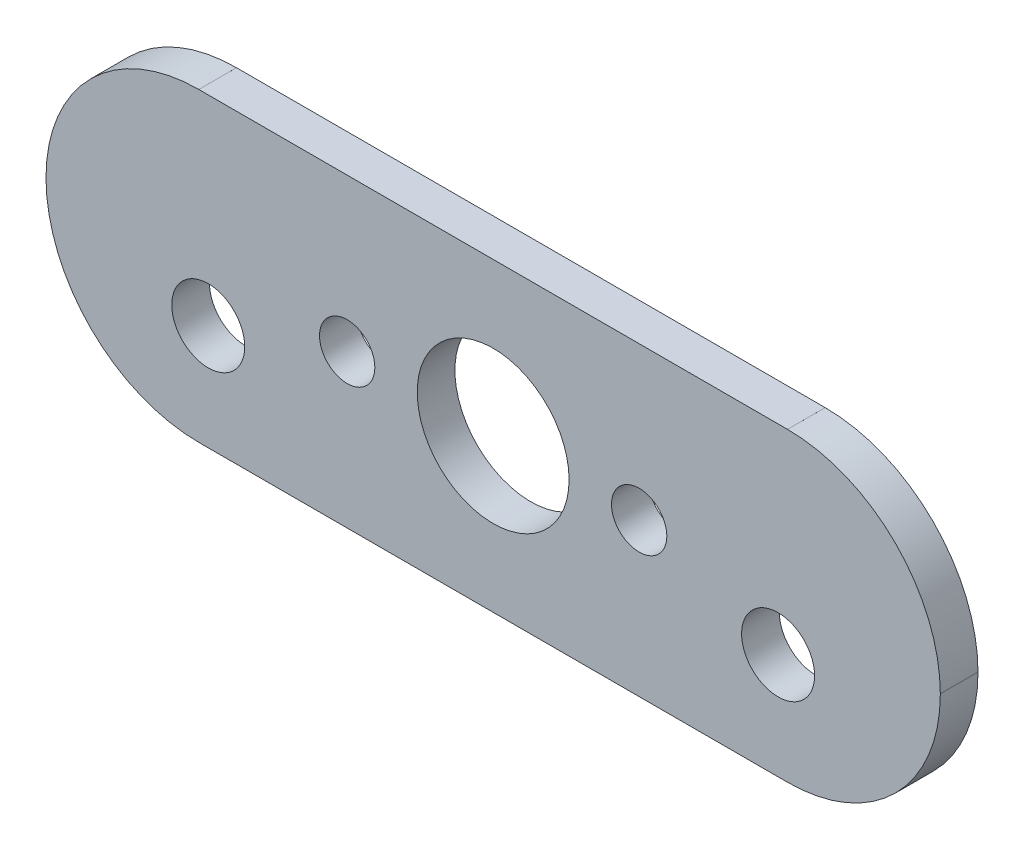
SolidWorks part; units mm, degrees
ref_plane "Alzado" through (0, 0, 0) normal (0, 0, 1) x (1, 0, 0)
ref_plane "Planta" through (0, 0, 0) normal (0, 1, 0) x (1, 0, 0)
ref_plane "Vista lateral" through (0, 0, 0) normal (1, 0, 0) x (0, 0, -1)
sketch "Model" plane through (0, 0, 0) normal (0, 0, 1) x (1, 0, 0)
  line L0 (18.99, 0.0199) -> (18.99, -0.0001)
  line L1 (12.5, 6.4901) -> (-12.5, 6.4901)
  line L2 (-18.9901, 0.01) -> (-18.9901, -0.01)
  line L3 (-12.5, -6.4902) -> (12.5, -6.4901)
  line L4 (0, -6.4902) -> (0, -7.9957) construction
  line L5 (0, 6.4901) -> (0, 6.0396)
  line L6 (0, 0) -> (0, 5.064) construction
  circle A0 centre (0, 0) radius 3.225
  circle A1 centre (-12.1, -2) radius 1.55
  circle A2 centre (12.1, -2) radius 1.55
  circle A3 centre (6.2, 0) radius 1.175
  circle A4 centre (-6.2, 0) radius 1.175
  arc A5 (12.5, -6.4901) -> (18.99, -0.0001) centre (12.4998, 0) ccw
  arc A6 (12.5, -6.4898) -> (12.5, -6.4904) centre (12.5, -6.4901) ccw
  arc A7 (20.6903, -0.01) -> (20.6898, -0.01) centre (20.6901, -0.01) ccw
  arc A8 (20.6898, -0.01) -> (20.6903, -0.01) centre (20.6901, -0.01) ccw
  arc A9 (20.6903, 0.01) -> (20.6898, 0.01) centre (20.6901, 0.01) ccw
  arc A10 (18.99, 0.0199) -> (12.5, 6.4901) centre (12.4999, 0) ccw
  arc A11 (20.6898, 0.01) -> (20.6903, 0.01) centre (20.6901, 0.01) ccw
  arc A12 (12.5, 6.4904) -> (12.5, 6.4898) centre (12.5, 6.4901) ccw
  arc A13 (-12.5, 6.4904) -> (-12.5, 6.4898) centre (-12.5, 6.4901) ccw
  arc A14 (12.5, 6.4898) -> (12.5, 6.4904) centre (12.5, 6.4901) ccw
  arc A15 (-12.5, 6.4901) -> (-18.9901, 0.01) centre (-12.5, 0) ccw
  arc A16 (-12.5, 6.4898) -> (-12.5, 6.4904) centre (-12.5, 6.4901) ccw
  arc A17 (-20.6903, 0.01) -> (-20.6898, 0.01) centre (-20.6901, 0.01) ccw
  arc A18 (-20.6903, -0.01) -> (-20.6898, -0.01) centre (-20.6901, -0.01) ccw
  arc A19 (-20.6898, 0.01) -> (-20.6903, 0.01) centre (-20.6901, 0.01) ccw
  arc A20 (-18.9901, -0.01) -> (-12.5, -6.4902) centre (-12.5, 0) ccw
  arc A21 (-20.6898, -0.01) -> (-20.6903, -0.01) centre (-20.6901, -0.01) ccw
  arc A22 (-12.5, -6.4905) -> (-12.5, -6.4899) centre (-12.5, -6.4902) ccw
  arc A23 (12.5, -6.4904) -> (12.5, -6.4898) centre (12.5, -6.4901) ccw
  arc A24 (-12.5, -6.4899) -> (-12.5, -6.4905) centre (-12.5, -6.4902) ccw
  circle A26 centre (0, 0) radius 3.2
  circle A27 centre (-6.2, 0) radius 1.175
  circle A28 centre (6.2, 0) radius 1.175
  dimension "D1" = 6.45
  dimension "D2" = 2.35
  dimension "D4" = 3.1
  dimension "D5" = 25
  dimension "D6" = 25
  dimension "D7" = 12.1
  dimension "D9" = 2
  dimension "D10" = 6.4901
  dimension "D11" = 6.4902
extrude "Saliente-Extruir1" add sketch "Model" along normal blind 1.6
sketch "Croquis3" plane through (0, 0, 1.6) normal (0, 0, 1) x (1, 0, 0)
  circle A0 centre (-12.1, -2) radius 1.55
